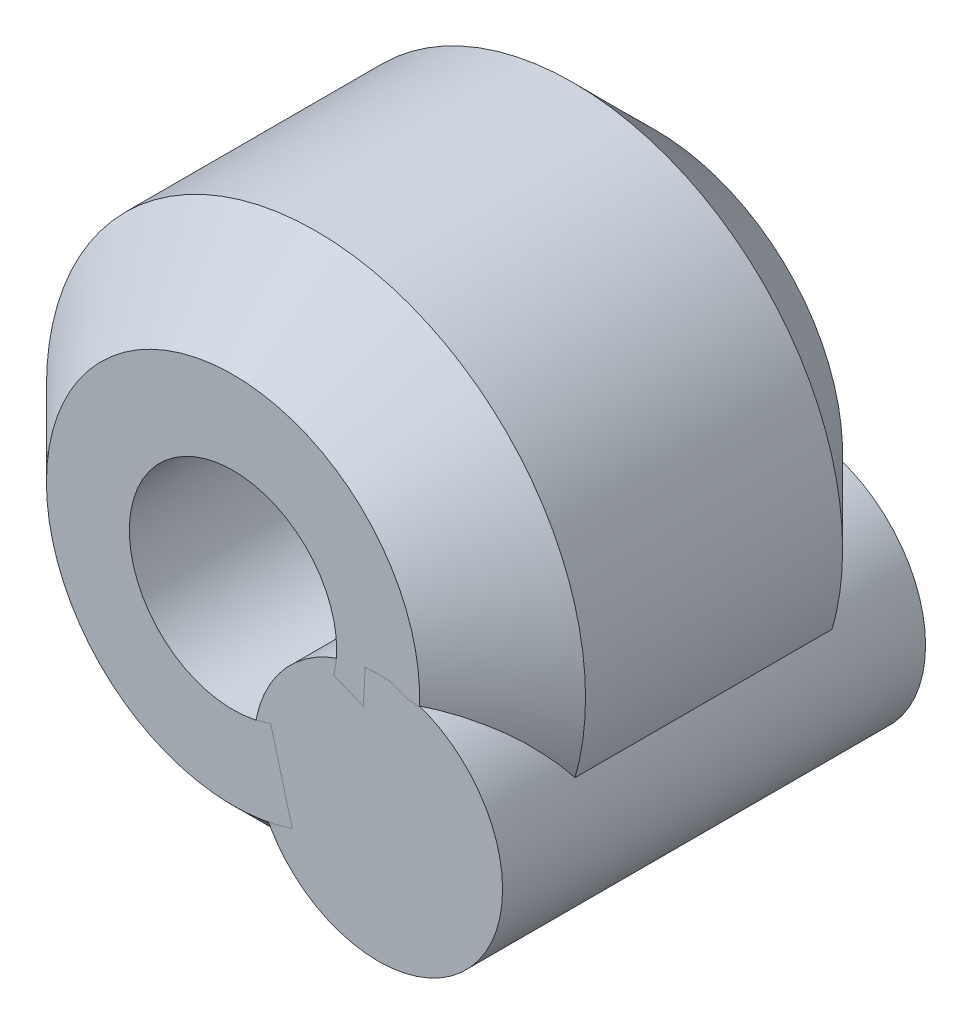
SolidWorks part; units mm, degrees
ref_plane "Front Plane" through (0, 0, 0) normal (0, 0, 1) x (1, 0, 0)
ref_plane "Top Plane" through (0, 0, 0) normal (0, 1, 0) x (1, 0, 0)
ref_plane "Right Plane" through (0, 0, 0) normal (1, 0, 0) x (0, 0, -1)
sketch "Sketch1" plane through (0, 0, 0) normal (0, 1, 0) x (1, 0, 0)
  line L0 (-8, -3.1) -> (-10, -5.1)
  line L1 (-10, 5.1) -> (-8, 3.1)
  line L2 (-8, 3.1) -> (-8, -3.1)
  line L3 (0, 0) -> (-8, 0) construction
  line L4 (8, 3.1) -> (8, -3.1) construction
  line L5 (8, -3.1) -> (10, -5.1) construction
  line L6 (8, 3.1) -> (10, 5.1) construction
  line L7 (0, 0) -> (8, 0) construction
  line L13 (-10, 5.1) -> (-14.5, 5.1)
  line L14 (-14.5, 5.1) -> (-14.5, -5.1)
  line L15 (-14.5, -5.1) -> (-10, -5.1)
  dimension "D1" = 135
  dimension "D2" = 135
  dimension "D3" = 135
  dimension "D4" = 10
  dimension "D5" = 5.1
  dimension "D6" = 6.2
  dimension "D7" = 16
  dimension "D8" = 4.5
sketch "Sketch3" plane through (0, 0, 0) normal (0, 0, 1) x (1, 0, 0)
  line L0 (-8, 0) -> (-8, -6.1581) construction
  line L1 (-8, 0) -> (-10, 0) construction
  line L2 (-15.5247, 0) -> (10, 0) construction
  line L3 (-10, 0) -> (-8, 0) construction
  circle A0 centre (-11, -3) radius 3
  dimension "D1" = 6
extrude "Boss-Extrude1" add sketch "Sketch3" along normal up to vertex (5.1 mm away) and the other way up to vertex (5.1 mm away) up to point (-10, 0, 5.1) other way up to point (-10, 0, -5.1)
revolve "Revolve1" add sketch "Sketch1" angle 360 about L14
sketch "Sketch7" plane through (0, 0, 0) normal (0, 0, 1) x (1, 0, 0)
  circle A0 centre (-14.5, 0) radius 2.5
  point P0 (-14.5, 0)
  dimension "D1" = 5
extrude "Cut-Extrude1" cut sketch "Sketch7" against normal through all both and the other way through all
